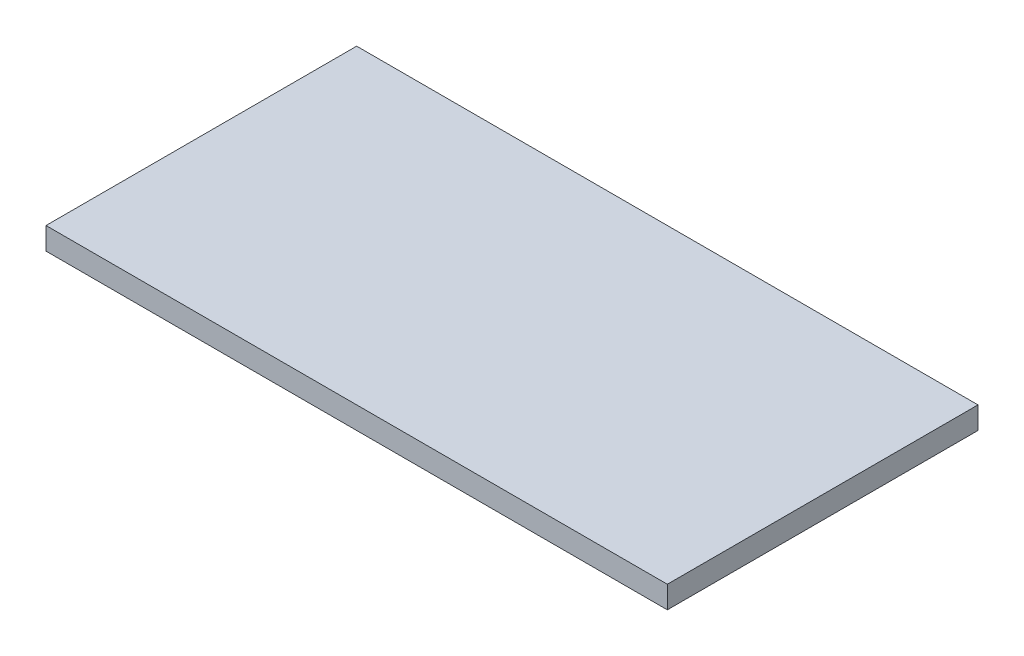
SolidWorks part; units mm, degrees
ref_plane "Front Plane" through (0, 0, 0) normal (0, 0, 1) x (1, 0, 0)
ref_plane "Top Plane" through (0, 0, 0) normal (0, 1, 0) x (1, 0, 0)
ref_plane "Right Plane" through (0, 0, 0) normal (1, 0, 0) x (0, 0, -1)
sketch "Sketch1" plane through (0, 0, 0) normal (0, 1, 0) x (1, 0, 0)
  line L1 (0, 0) -> (56, 0)
  line L2 (0, 0) -> (0, 28)
  line L3 (0, 28) -> (56, 28)
  line L4 (56, 0) -> (56, 28)
  dimension "D1" = 56
  dimension "D2" = 28
extrude "Boss-Extrude1" add sketch "Sketch1" along normal blind 2
